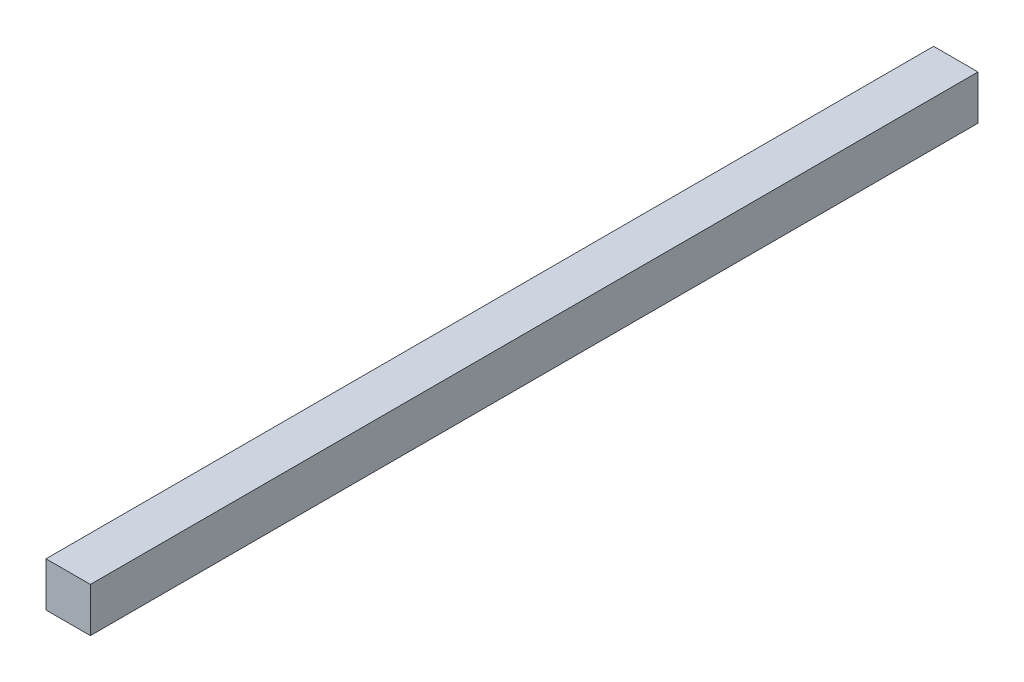
SolidWorks part; units mm, degrees
ref_plane "Front Plane" through (0, 0, 0) normal (0, 0, 1) x (1, 0, 0)
ref_plane "Top Plane" through (0, 0, 0) normal (0, 1, 0) x (1, 0, 0)
ref_plane "Right Plane" through (0, 0, 0) normal (1, 0, 0) x (0, 0, -1)
sketch "Sketch1" plane through (0, 0, 0) normal (0, 0, 1) x (1, 0, 0)
  line L1 (-2.5, -2.5) -> (2.5, -2.5)
  line L2 (-2.5, -2.5) -> (-2.5, 2.5)
  line L3 (-2.5, 2.5) -> (2.5, 2.5)
  line L4 (2.5, -2.5) -> (2.5, 2.5)
  line L5 (-2.5, -2.5) -> (2.5, 2.5) construction
  line L6 (-2.5, 2.5) -> (2.5, -2.5) construction
  point P0 (0, 0)
  dimension "D1" = 5
  dimension "D2" = 5
extrude "Boss-Extrude1" add sketch "Sketch1" along normal blind 100
